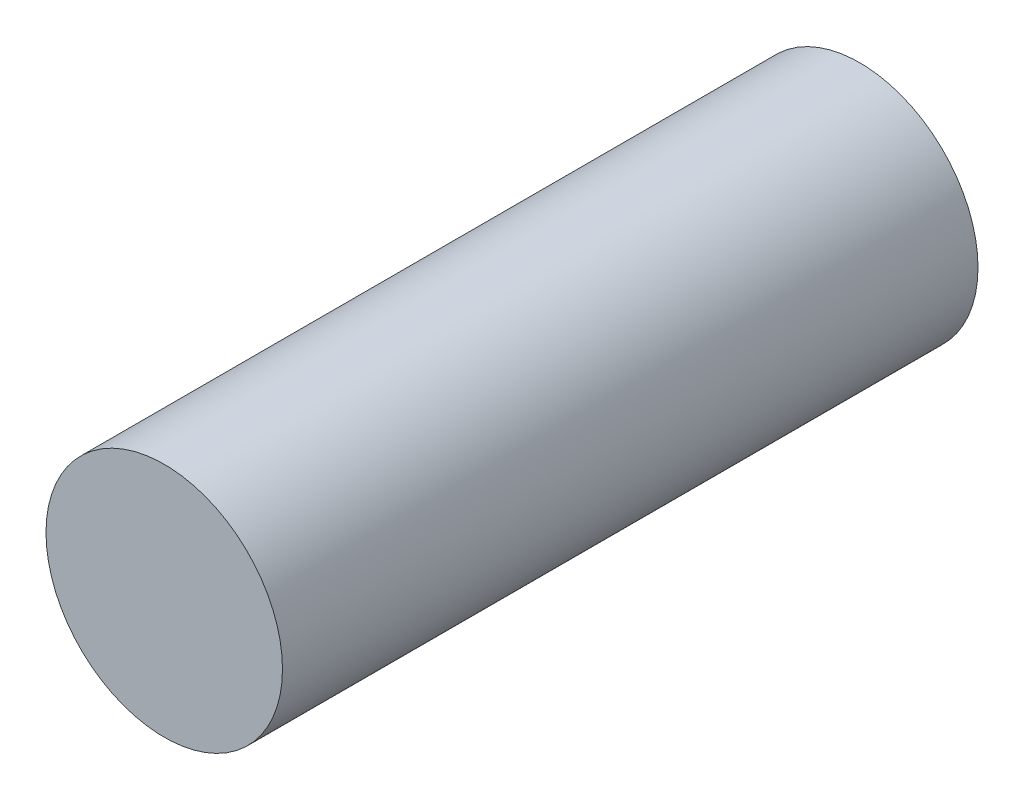
SolidWorks part; units mm, degrees
material "ASTM A36 Steel"
ref_plane "Front Plane" through (0, 0, 0) normal (0, 0, 1) x (1, 0, 0)
ref_plane "Top Plane" through (0, 0, 0) normal (0, 1, 0) x (1, 0, 0)
ref_plane "Right Plane" through (0, 0, 0) normal (1, 0, 0) x (0, 0, -1)
sketch "Sketch1" plane through (0, 0, 0) normal (0, 0, 1) x (1, 0, 0)
  circle A0 centre (0, 0) radius 4.25
  dimension "D1" = 8.5
extrude "Boss-Extrude1" add sketch "Sketch1" along normal blind 25
